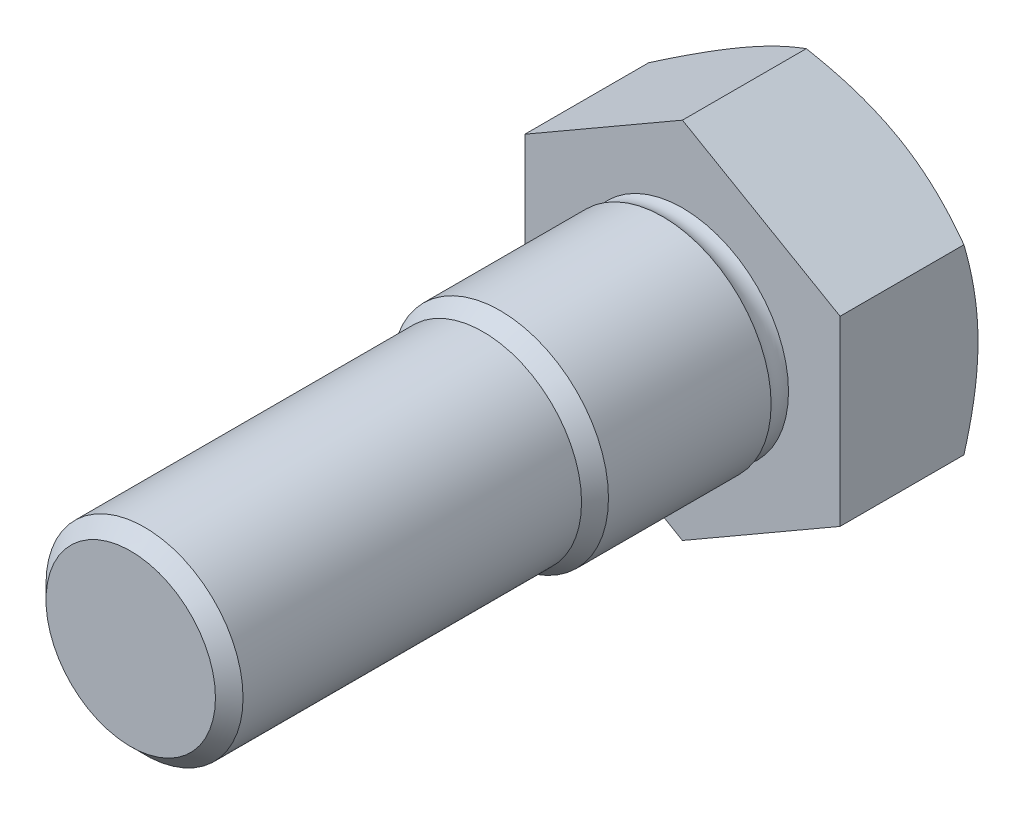
SolidWorks part; units mm, degrees
ref_plane "Přední rovina" through (0, 0, 0) normal (0, 0, 1) x (1, 0, 0)
ref_plane "Vrchní rovina" through (0, 0, 0) normal (0, 1, 0) x (1, 0, 0)
ref_plane "Pravá rovina" through (0, 0, 0) normal (1, 0, 0) x (0, 0, -1)
sketch "Skica1" plane through (0, 0, 0) normal (0, 0, 1) x (1, 0, 0)
  line L1 (8, -4.6188) -> (8, 4.6188)
  line L2 (8, 4.6188) -> (0, 9.2376)
  line L3 (0, 9.2376) -> (-8, 4.6188)
  line L4 (-8, 4.6188) -> (-8, -4.6188)
  line L5 (-8, -4.6188) -> (0, -9.2376)
  line L6 (0, -9.2376) -> (8, -4.6188)
  circle A0 centre (0, 0) radius 8 construction
  dimension "s" = 16
extrude "Vysunout1" add sketch "Skica1" along normal blind 7
sketch "Skica2" plane through (0, 0, 0) normal (0, 1, 0) x (1, 0, 0)
  line L0 (8, 0) -> (20.1244, 0)
  line L1 (20.1244, 0) -> (20.1244, -7)
  line L2 (20.1244, -7) -> (8, 0)
  line L3 (8, -7) -> (0, -7) construction
  line L4 (0, 0) -> (0, -7) construction
  dimension "D1" = 30
revolve "Odebrat otočením1" cut sketch "Skica2" angle 360 about L4
sketch "Skica5" plane through (0, 0, 7) normal (0, 0, 1) x (1, 0, 0)
  circle A0 centre (0, 0) radius 5
  dimension "M" = 10
extrude "Vysunout4" add sketch "Skica5" along normal blind 28
cosmetic thread "Kosmetický závit1" parameters "b"=16, "D2"=8.5
chamfer "Zkosit1" distance 0.7 angle 45 1 edges at (5, 0, 35)
sketch "Skica3" plane through (0, 0, 7) normal (0, 0, 1) x (1, 0, 0)
  circle A0 centre (0, 0) radius 5.3
  dimension "d3" = 10.6
extrude "Vysunout2" add sketch "Skica3" along normal blind 1
ref_plane "Rovina1" through (0, 0, 17.12) normal (0, 0, 1) x (1, 0, 0)
sketch "Skica4" plane through (0, 0, 8) normal (0, 0, 1) x (1, 0, 0)
  circle A0 centre (0, 0) radius 5.5
  dimension "d2" = 11
extrude "Vysunout3" add sketch "Skica4" along normal up to surface (9.12 mm away) up to plane "Rovina1"
sketch "Skica6" plane through (0, 0, 0) normal (0, 1, 0) x (1, 0, 0)
  line L0 (-5.5, -17.12) -> (-5.5, -16.254)
  line L1 (-5.5, -16.254) -> (-5, -17.12)
  line L2 (-5, -17.12) -> (-5.5, -17.12)
  line L3 (0, -17.12) -> (0, -8) construction
  line L4 (-5.5, -17.12) -> (5.5, -17.12) construction
  line L5 (5.5, -8) -> (-5.5, -8) construction
  dimension "D1" = 30
revolve "Odebrat otočením2" cut sketch "Skica6" angle 360 about L3
sketch "Skica7" plane through (0, 0, 0) normal (0, 1, 0) x (1, 0, 0)
  line L0 (8, -7) -> (0, -7) construction
  line L1 (5.3, -8) -> (5.3, -7) construction
  line L2 (5.3835, -7) -> (5.3, -7)
  line L3 (5.3, -7) -> (5.3, -8)
  line L4 (5.5, -8) -> (-5.5, -8) construction
  line L5 (5.3, -8) -> (5.5, -8)
  line L6 (0, -16.254) -> (0, -8) construction
  line L7 (5.5, -16.254) -> (-5.5, -16.254) construction
  arc A0 (5.5, -8) -> (5.3835, -7) centre (6.3, -7.4) cw
  dimension "D1" = 1
revolve "Otočit kolem osy1" add sketch "Skica7" angle 360 about L6
equation "\"D1@Zkosit1\" = 0.07 * \"M@Skica5\""
equation "\"D1@Skica7\" = \"r@Vysunout2\""
equation "\"D2@Kosmetický závit1\" = 0.85 * \"M@Skica5\""
